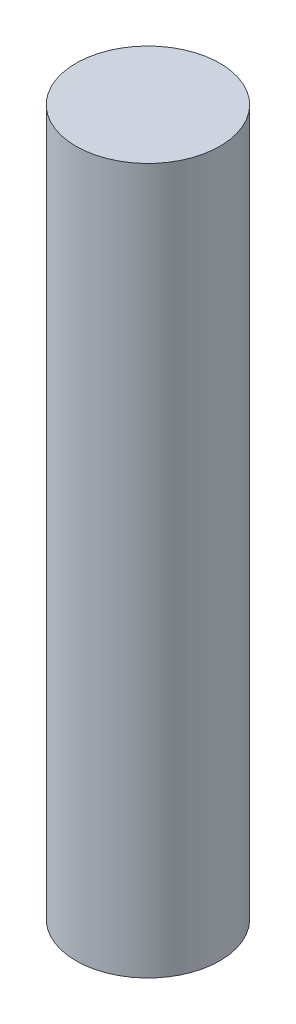
SolidWorks part; units mm, degrees
ref_plane "Front Plane" through (0, 0, 0) normal (0, 0, 1) x (1, 0, 0)
ref_plane "Top Plane" through (0, 0, 0) normal (0, 1, 0) x (1, 0, 0)
ref_plane "Right Plane" through (0, 0, 0) normal (1, 0, 0) x (0, 0, -1)
sketch "Sketch1" plane through (0, 0, 0) normal (0, 1, 0) x (1, 0, 0)
  circle A0 centre (0, 0) radius 2.55
  dimension "D1" = 5.1
extrude "Boss-Extrude1" add sketch "Sketch1" along normal blind 25
